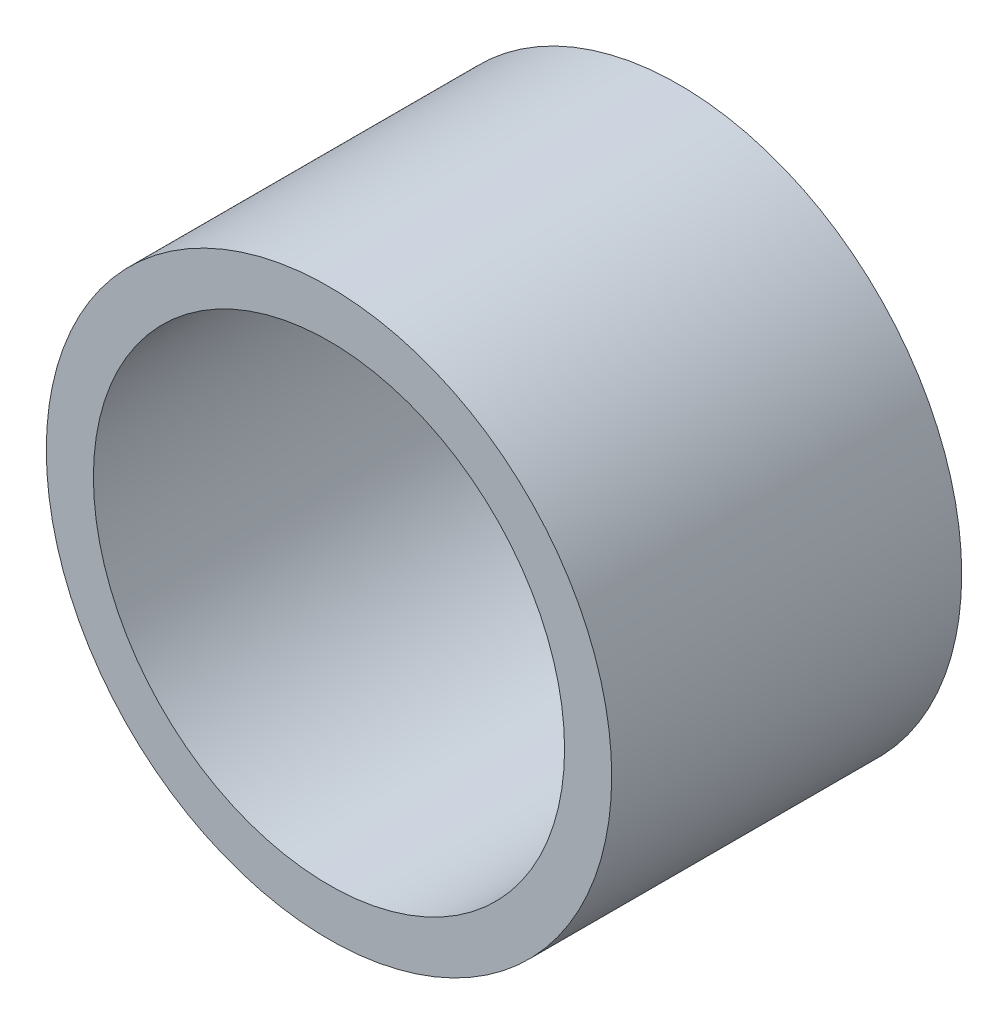
SolidWorks part; units mm, degrees
material "Brass"
ref_plane "Front Plane" through (0, 0, 0) normal (0, 0, 1) x (1, 0, 0)
ref_plane "Top Plane" through (0, 0, 0) normal (0, 1, 0) x (1, 0, 0)
ref_plane "Right Plane" through (0, 0, 0) normal (1, 0, 0) x (0, 0, -1)
sketch "Sketch1" plane through (0, 0, 0) normal (0, 0, 1) x (1, 0, 0)
  circle A0 centre (0, 0) radius 21
  circle A1 centre (0, 0) radius 17.5
  dimension "D1" = 42
  dimension "D2" = 35
extrude "Boss-Extrude1" add sketch "Sketch1" along normal blind 26
